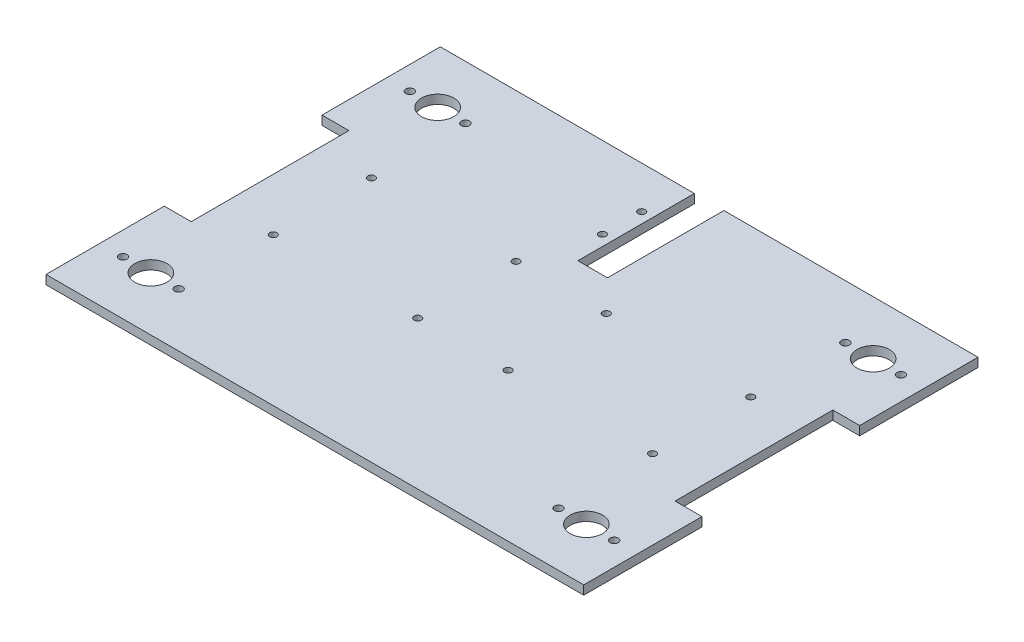
SolidWorks part; units mm, degrees
ref_plane "Front Plane" through (0, 0, 0) normal (0, 0, 1) x (1, 0, 0)
ref_plane "Top Plane" through (0, 0, 0) normal (0, 1, 0) x (1, 0, 0)
ref_plane "Right Plane" through (0, 0, 0) normal (1, 0, 0) x (0, 0, -1)
sketch "Sketch1" plane through (0, 0, 0) normal (0, 1, 0) x (1, 0, 0)
  line L1 (150, 110) -> (-150, 110)
  line L2 (150, 110) -> (150, -110)
  line L3 (150, -110) -> (-150, -110)
  line L4 (-150, 110) -> (-150, -110)
  point P0 (0, 0)
  dimension "D1" = 300
  dimension "D2" = 220
extrude "Boss-Extrude1" add sketch "Sketch1" along normal blind 5
sketch "Sketch2" plane through (0, 5, 0) normal (0, 1, 0) x (1, 0, 0)
  line L0 (-150, 110) -> (-150, -110) construction
  line L1 (-135, -44) -> (-150, -44)
  line L2 (-135, -44) -> (-135, 44)
  line L3 (-135, 44) -> (-150, 44)
  line L4 (-150, -44) -> (-150, 44)
  line L5 (-135, -44) -> (-150, 44) construction
  line L6 (-135, 44) -> (-150, -44) construction
  line L7 (150, -110) -> (150, 110) construction
  line L8 (135, -44) -> (150, -44)
  line L9 (135, -44) -> (135, 44)
  line L10 (135, 44) -> (150, 44)
  line L11 (150, -44) -> (150, 44)
  line L12 (135, -44) -> (150, 44) construction
  line L13 (135, 44) -> (150, -44) construction
  line L14 (142.5, 0) -> (-142.5, 0) construction
  point P0 (-142.5, 0)
  point P7 (142.5, 0)
  dimension "D1" = 15
  dimension "D2" = 88
extrude "Cut-Extrude1" cut sketch "Sketch2" against normal blind 10
sketch "Esquisse1" plane through (0, 5, 0) normal (0, 1, 0) x (1, 0, 0)
  line L0 (-292.7369, 0) -> (274.1208, 0) construction
sketch "Esquisse2" plane through (0, 5, 0) normal (0, 1, 0) x (1, 0, 0)
  line L0 (-135, -44) -> (-135, 44) construction
  line L1 (135, 44) -> (135, -44) construction
  line L3 (-216.2328, 0) -> (312.8741, 0) construction
  line L4 (-292.7369, 0) -> (274.1208, 0) construction
  circle A0 centre (-105.8, 27.4) radius 2
  circle A1 centre (-25.2, 27.4) radius 2
  circle A2 centre (-25.2, -27.4) radius 2
  circle A3 centre (-105.8, -27.4) radius 2
  circle A4 centre (25.2, -27.4) radius 2
  circle A5 centre (105.8, -27.4) radius 2
  circle A6 centre (25.2, 27.4) radius 2
  circle A7 centre (105.8, 27.4) radius 2
  dimension "D1" = 54.8
  dimension "D2" = 54.8
  dimension "D3" = 54.8
  dimension "D4" = 29.2
  dimension "D5" = 80.6
  dimension "D6" = 80.6
  dimension "D7" = 29.2
  dimension "D8" = 80.6
  dimension "D9" = 29.2
extrude "Enlèv. mat.-Extru.1" cut sketch "Esquisse2" against normal blind 10
sketch "Esquisse4" plane through (0, 5, 0) normal (0, 1, 0) x (1, 0, 0)
  line L0 (-39.8032, 0) -> (52.4625, 0) construction
  line L1 (-150, 110) -> (-150, 44) construction
  line L3 (150, 44) -> (150, 110) construction
  line L9 (-8.25, 110) -> (8.25, 110)
  line L10 (8.25, 110) -> (8.25, 45)
  line L11 (-8.25, 45) -> (8.25, 45)
  line L12 (-8.25, 110) -> (-8.25, 45)
  line L13 (-292.7369, 0) -> (274.1208, 0) construction
  line L14 (150, 110) -> (-150, 110) construction
  dimension "D1" = 65
  dimension "D2" = 0
  dimension "D3" = 16.5
  dimension "D4" = 141.75
  dimension "D5" = 141.75
extrude "Enlèv. mat.-Extru.4" cut sketch "Esquisse4" against normal up to surface (5 mm away) up to face at (25.2, 0, 25.4)
sketch "Esquisse5" plane through (0, 5, 0) normal (0, 1, 0) x (1, 0, 0)
  line L3 (-13.1495, 0) -> (-7.2334, 0)
  circle A0 centre (-14.1661, 86.5376) radius 2
  circle A1 centre (-14.1661, 64.6456) radius 2
  dimension "D1" = 21.892
extrude "Enlèv. mat.-Extru.5" cut sketch "Esquisse5" against normal blind 10 contours A0 | A1
sketch "Esquisse6" plane through (0, 5, 0) normal (0, 1, 0) x (1, 0, 0)
  circle A0 centre (-137, -80) radius 2.25
  circle A1 centre (-106, -80) radius 2.25
  circle A2 centre (106, -80) radius 2.25
  circle A3 centre (137, -80) radius 2.25
  circle A4 centre (137, 80) radius 2.25
  circle A5 centre (106, 80) radius 2.25
  circle A6 centre (-106, 80) radius 2.25
  circle A7 centre (-137, 80) radius 2.25
  dimension "D1" = 4.5
  dimension "D2" = 4.5
extrude "Enlèv. mat.-Extru.6" cut sketch "Esquisse6" against normal blind 10
sketch "Esquisse7" plane through (0, 5, 0) normal (0, 1, 0) x (1, 0, 0)
  circle A1 centre (-121.5, 80) radius 9
  circle A2 centre (-121.5, -80) radius 9
  circle A3 centre (121.5, -80) radius 9
  circle A4 centre (121.5, 80) radius 9
extrude "Enlèv. mat.-Extru.9" cut sketch "Esquisse7" against normal blind 10
